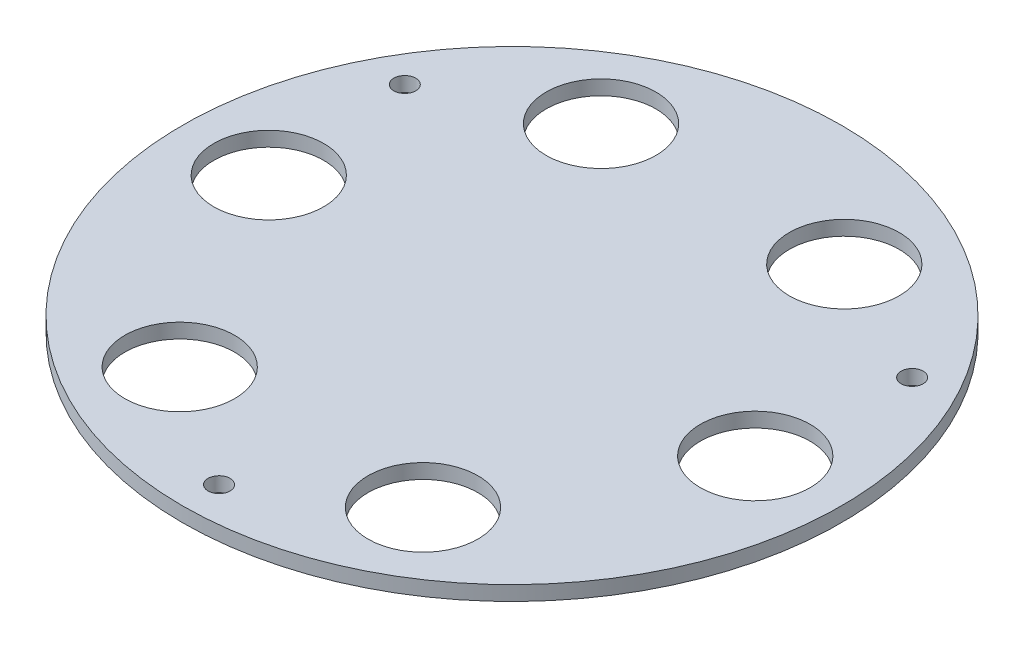
SolidWorks part; units mm, degrees
ref_plane "Front Plane" through (0, 0, 0) normal (0, 0, 1) x (1, 0, 0)
ref_plane "Top Plane" through (0, 0, 0) normal (0, 1, 0) x (1, 0, 0)
ref_plane "Right Plane" through (0, 0, 0) normal (1, 0, 0) x (0, 0, -1)
sketch "Sketch1" plane through (0, 0, 0) normal (0, 1, 0) x (1, 0, 0)
  circle A0 centre (0, 0) radius 45
  dimension "D1" = 90
extrude "Boss-Extrude1" add sketch "Sketch1" against normal blind 2 contours A0
sketch "Sketch2" plane through (0, 0, 0) normal (0, 1, 0) x (1, 0, 0)
  circle A0 centre (0, 0) radius 33.2139
  point P3 (16.607, 28.7641)
  point P4 (-16.607, 28.7641)
  point P5 (-33.2139, 0)
  point P6 (-16.607, -28.7641)
  point P7 (16.607, -28.7641)
  point P8 (33.2139, 0)
hole_wizard "Ø8.0mm Dowel Hole1" positions "Sketch3" profile "Sketch4" hole size "Ø8.0" standard "ANSI Metric" end condition through all
sketch "Sketch3" plane through (0, 0, 0) normal (0, 1, 0) x (1, 0, 0)
  point P0 (-16.607, 28.7641)
  point P3 (-16.607, -28.7641)
  point P6 (33.2139, 0)
  point P9 (16.607, 28.7641)
  point P12 (16.607, -28.7641)
  point P15 (-33.2139, 0)
sketch "Sketch4" plane through (-16.607, 0, -28.7641) normal (1, 0, 0) x (0, 0, 1)
  line L0 (0, 0) -> (0, 2)
  line L1 (0, 2) -> (7.5, 2)
  line L2 (7.5, 2) -> (7.5, 0)
  line L5 (7.5, 0) -> (0, 0)
  line L11 (0, -6.35) -> (0, 107.95) construction
  dimension "Thru Hole Dia." = 15
  dimension "Thru Hole Depth" = 2
sketch "Sketch10" plane through (0, 0, 0) normal (0, 1, 0) x (1, 0, 0)
  circle A0 centre (0, 0) radius 40
  point P3 (-34.641, 20)
  point P4 (0, -40)
  point P5 (34.641, 20)
hole_wizard "Ø3.0 (3) Diameter Hole1" positions "Sketch11" profile "Sketch12" hole size "Ø3.0" standard "ANSI Metric" end condition through all
sketch "Sketch11" plane through (0, 0, 0) normal (0, 1, 0) x (1, 0, 0)
  point P0 (-34.641, 20)
  point P3 (0, -40)
  point P6 (34.641, 20)
sketch "Sketch12" plane through (-34.641, 0, -20) normal (1, 0, 0) x (0, 0, 1)
  line L0 (0, 0) -> (0, 2)
  line L1 (0, 2) -> (1.5, 2)
  line L2 (1.5, 2) -> (1.5, 0)
  line L5 (1.5, 0) -> (0, 0)
  line L11 (0, -6.35) -> (0, 107.95) construction
  dimension "Thru Hole Dia." = 3
  dimension "Thru Hole Depth" = 2
